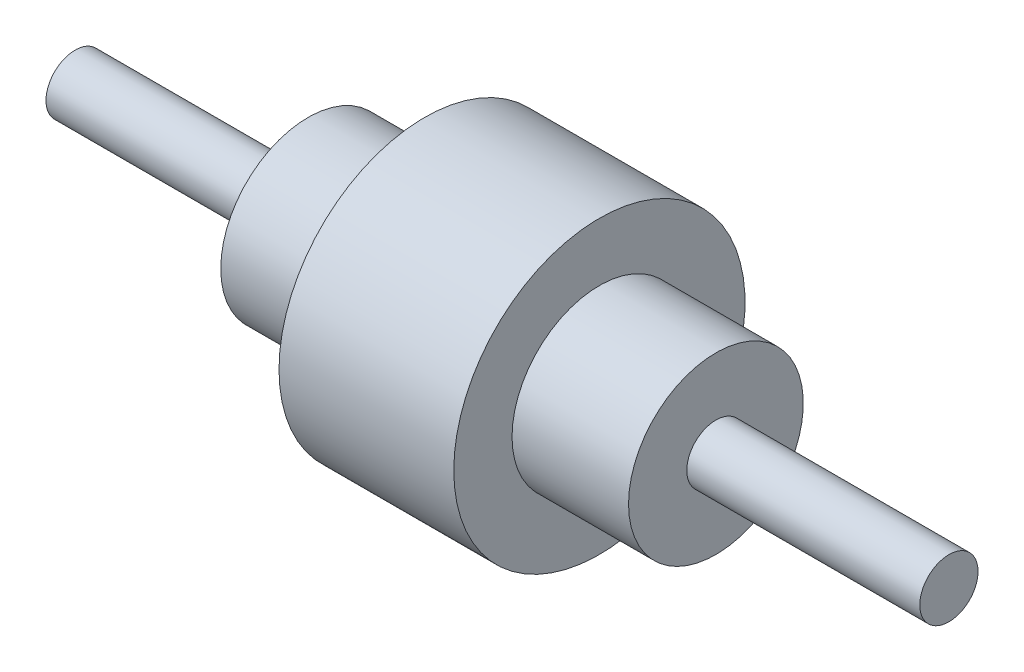
SolidWorks part; units mm, degrees
ref_plane "前基準面" through (0, 0, 0) normal (0, 0, 1) x (1, 0, 0)
ref_plane "上基準面" through (0, 0, 0) normal (0, 1, 0) x (1, 0, 0)
ref_plane "右基準面" through (0, 0, 0) normal (1, 0, 0) x (0, 0, -1)
sketch "草圖1" plane through (0, 0, 0) normal (0, 0, 1) x (1, 0, 0)
  line L1 (0, 0) -> (80, 0)
  line L2 (0, 0) -> (0, 10)
  line L3 (0, 10) -> (80, 10)
  line L4 (80, 0) -> (80, 10)
  line L5 (80, 0) -> (120, 0)
  line L6 (80, 0) -> (80, 30)
  line L7 (80, 30) -> (120, 30)
  line L8 (120, 0) -> (120, 30)
  line L9 (120, 0) -> (180, 0)
  line L10 (120, 0) -> (120, 50)
  line L11 (120, 50) -> (180, 50)
  line L12 (180, 0) -> (180, 50)
  line L13 (180, 0) -> (220, 0)
  line L14 (180, 0) -> (180, 30)
  line L15 (180, 30) -> (220, 30)
  line L16 (220, 0) -> (220, 30)
  line L17 (220, 0) -> (300, 0)
  line L18 (220, 0) -> (220, 10)
  line L19 (220, 10) -> (300, 10)
  line L20 (300, 0) -> (300, 10)
  point P17 (27.9248, 16.7252)
  dimension "D1" = 40
  dimension "D2" = 60
  dimension "D3" = 10
  dimension "D4" = 30
  dimension "D5" = 50
  dimension "D6" = 40
  dimension "D7" = 80
  dimension "D8" = 20
  dimension "D9" = 30
  dimension "D10" = 80
revolve "旋轉1" add sketch "草圖1" angle 360 about L1
